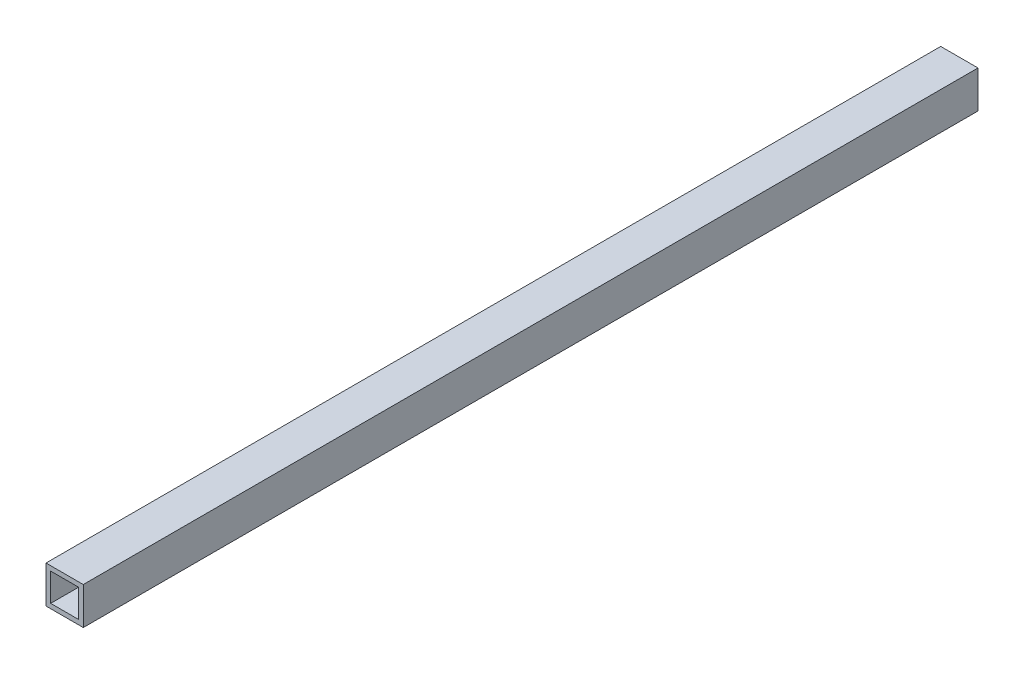
SolidWorks part; units mm, degrees
ref_plane "Front Plane" through (0, 0, 0) normal (0, 0, 1) x (1, 0, 0)
ref_plane "Top Plane" through (0, 0, 0) normal (0, 1, 0) x (1, 0, 0)
ref_plane "Right Plane" through (0, 0, 0) normal (1, 0, 0) x (0, 0, -1)
sketch "Sketch1" plane through (0, 0, 0) normal (0, 0, 1) x (1, 0, 0)
  line L1 (-12.7, 12.7) -> (12.7, 12.7)
  line L2 (-12.7, 12.7) -> (-12.7, -12.7)
  line L3 (-12.7, -12.7) -> (12.7, -12.7)
  line L4 (12.7, 12.7) -> (12.7, -12.7)
  line L5 (-12.7, 12.7) -> (12.7, -12.7) construction
  line L6 (-12.7, -12.7) -> (12.7, 12.7) construction
  line L7 (-9.525, -9.525) -> (9.525, -9.525)
  line L8 (-9.525, -9.525) -> (-9.525, 9.525)
  line L9 (-9.525, 9.525) -> (9.525, 9.525)
  line L10 (9.525, -9.525) -> (9.525, 9.525)
  line L11 (-9.525, -9.525) -> (9.525, 9.525) construction
  line L12 (-9.525, 9.525) -> (9.525, -9.525) construction
  point P0 (0, 0)
  point P6 (0, 0)
  dimension "D1" = 25.4
  dimension "D2" = 25.4
  dimension "D3" = 19.05
extrude "Boss-Extrude1" add sketch "Sketch1" along normal blind 609.6
